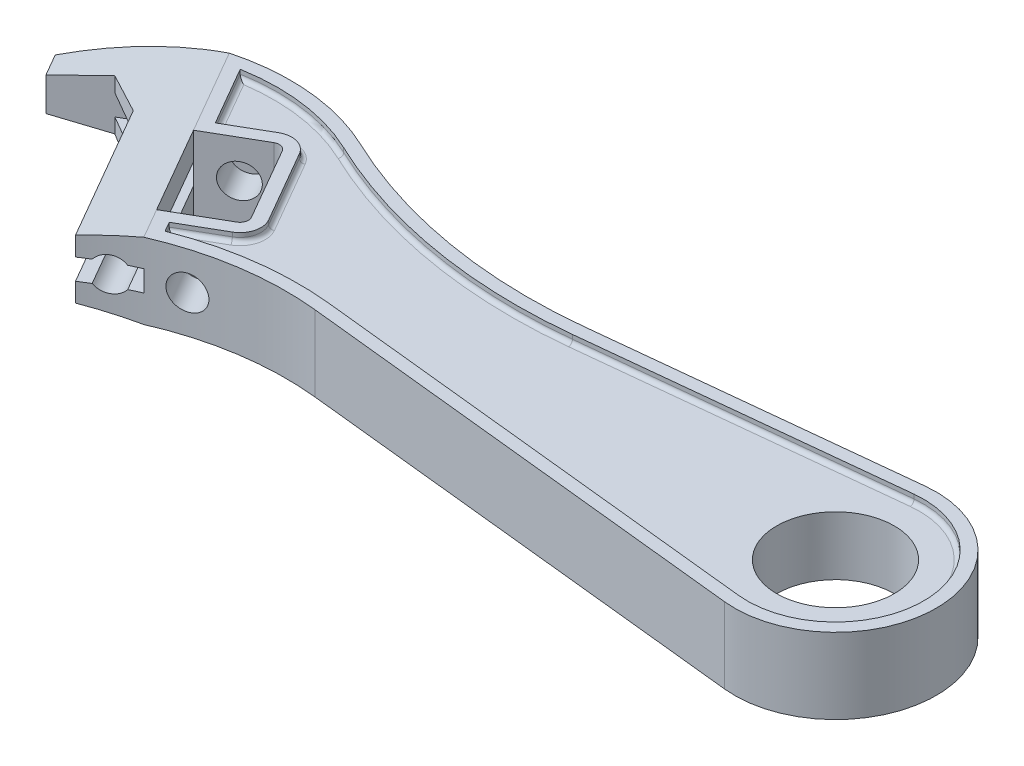
SolidWorks part; units mm, degrees
ref_plane "Front Plane" through (0, 0, 0) normal (0, 0, 1) x (1, 0, 0)
ref_plane "Top Plane" through (0, 0, 0) normal (0, 1, 0) x (1, 0, 0)
ref_plane "Right Plane" through (0, 0, 0) normal (1, 0, 0) x (0, 0, -1)
sketch "Sketch1" plane through (0, 0, 0) normal (0, 1, 0) x (1, 0, 0)
  line L0 (-38.0501, 8.0669) -> (-1.2543, 11.9343)
  line L1 (-55.796, -6.2017) -> (-1.2543, -11.9343)
  line L2 (25.0779, 0) -> (-99.2521, 0) construction
  line L3 (-74.5814, 9.0764) -> (-68.5814, -1.3159)
  line L4 (-68.5814, -1.3159) -> (-75.5096, -5.3159)
  line L5 (-75.5096, -5.3159) -> (-81.5096, 5.0764)
  line L6 (-81.5096, 5.0764) -> (-74.5814, 9.0764)
  line L7 (-87.3276, 15.1534) -> (-73.4285, -8.9206)
  line L8 (-78.7058, -11.78) -> (-88.1077, 4.5046)
  line L9 (-88.1077, 4.5046) -> (-93.3038, 7.5046)
  line L10 (-93.3038, 7.5046) -> (-98.5, 4.5046)
  line L11 (-98.5, 4.5046) -> (-100, 7.1027)
  line L12 (-93.3038, 7.5046) -> (-100.748, 20.3983) construction
  line L13 (-101.2059, 16) -> (-33.4804, 16) construction
  line L14 (-18.4207, -12) -> (11.6425, -12) construction
  line L15 (-90.2318, 14.1836) -> (-76.1316, -10.2386) construction
  line L16 (12, -12.8198) -> (12, 13.5746) construction
  line L17 (-100, 22.224) -> (-100, -5.3159) construction
  circle A0 centre (0, 0) radius 7
  arc A1 (-1.2543, -11.9343) -> (-1.2543, 11.9343) centre (0, 0) ccw
  arc A2 (-38.0501, 8.0669) -> (-70.1252, 13.5701) centre (-44.3218, 67.7382) cw
  arc A3 (-55.796, -6.2017) -> (-78.7058, -11.78) centre (-59.4545, -41.01) ccw
  arc A4 (-100, 7.1027) -> (-70.1252, 13.5701) centre (-80.8766, -9) cw
  point P31 (-72.0455, -3.3159)
  point P32 (-78.0455, 7.0764)
  dimension "D1" = 14
  dimension "D2" = 5
  dimension "D5" = 60
  dimension "D6" = 35
  dimension "D13" = 25
  dimension "D3" = 12
  dimension "D4" = 6
  dimension "D7" = 8
  dimension "D8" = 6
  dimension "D9" = 3
  dimension "D10" = 30
  dimension "D11" = 15
  dimension "D12" = 6
  dimension "D14" = 16
  dimension "D15" = 8
  dimension "D16" = 4
  dimension "D17" = 12
  dimension "D18" = 0.49
  dimension "D19" = 28
  dimension "D20" = 60
  dimension "D21" = 19
  dimension "D22" = 6
  dimension "D23" = 3
  dimension "D24" = 12
  dimension "D25" = 112
extrude "Boss-Extrude1" add sketch "Sketch1" along normal mid plane 9 contours A4 L7 L6 L3 L4 A3 L1 A1 L0 A2 A0 | A4 L11 L10 L9 L8 A3 L7 L5
sketch "Sketch2" plane through (-22.5755, 0, -39.102) normal (0.5, 0, 0.866) x (0.866, 0, -0.5)
  line L0 (0, 0) -> (-77.8625, 0) construction
  line L1 (-64.0512, 0) -> (-64.0512, 4.5) construction
  line L2 (-68.0512, 4.5) -> (-60.0512, 4.5) construction
  line L3 (-68.0512, 4.5) -> (-68.0512, -4.5) construction
  line L4 (-60.0512, 4.5) -> (-60.0512, -4.5) construction
  circle A0 centre (-64.0512, 0) radius 2
  dimension "D1" = 4
  dimension "D2" = 4
  dimension "D3" = 4
extrude "Cut-Extrude1" cut sketch "Sketch2" against normal blind 4 and the other way up to surface other way up to face at (-67.4929, 0, 7.9972)
sketch "Sketch3" plane through (-26.5755, 0, -46.0302) normal (0.5, 0, 0.866) x (0.866, 0, -0.5)
  line L0 (-83.0512, 0) -> (-56.4357, 0) construction
  line L1 (-83.0512, 4.5) -> (-83.0512, -4.5) construction
  line L2 (-77.0512, 1.25) -> (-72.6125, 1.25)
  line L4 (-77.0512, 4.5) -> (-77.0512, -4.5) construction
  line L5 (-77.0512, -1.25) -> (-72.6125, -1.25)
  line L6 (-69.49, 1.25) -> (-68.0512, 1.25)
  line L7 (-68.0512, 1.25) -> (-68.0512, -1.25)
  line L8 (-69.49, -1.25) -> (-68.0512, -1.25)
  circle A0 centre (-71.0512, 0) radius 2
  line M10 (-77.0512, -4.5) -> (-77.0512, 4.5)
  dimension "D1" = 4
  dimension "D2" = 2.5
  dimension "D3" = 2.5
  dimension "D4" = 15
  dimension "D5" = 12
extrude "Cut-Extrude2" cut sketch "Sketch3" along normal up to next contours A0 L0 | L0 A0 | L0 A0 L2 M10 | L0 L5 A0 M10 | A0 L0 L7 L6 | L0 A0 L8 L7
sketch "Sketch4" plane through (-26.5755, 0, -46.0302) normal (0.5, 0, 0.866) x (0.866, 0, -0.5)
  line L0 (-68.0512, 4.5) -> (-83.0512, 4.5)
  line L2 (-83.0512, 4.5) -> (-83.0512, -4.5) construction
  line L3 (-77.0512, 4.5) -> (-83.0512, 4.5) construction
  line L4 (-68.0512, 4.5) -> (-83.0512, 2)
  line L5 (-83.0512, 2) -> (-83.0512, 4.5)
  line L6 (0, 0) -> (-76.6034, 0) construction
  line L7 (-68.0512, -4.5) -> (-83.0512, -4.5)
  line L8 (-83.0512, -2) -> (-83.0512, -4.5)
  line L9 (-68.0512, -4.5) -> (-83.0512, -2)
  dimension "D1" = 15
  dimension "D2" = 2.5
extrude "Cut-Extrude3" cut sketch "Sketch4" against normal through all both and the other way through all
fillet "Fillet1" radius 1 2 edges at (-68.5814, 0, 1.3159) (-74.5814, 0, -9.0764)
sketch "Sketch5" plane through (0, 4.5, 0) normal (0, 1, 0) x (1, 0, 0)
  line L14 (-85.0071, 14.1342) -> (-80.9606, 7.1254)
  line L15 (-80.9606, 7.1254) -> (-76.1974, 9.8754)
  line L16 (-72.7824, 8.9604) -> (-67.7824, 0.3001)
  line L17 (-68.6974, -3.1149) -> (-73.4606, -5.8649)
  line L18 (-73.4606, -5.8649) -> (-72.7868, -7.032)
  line L19 (-55.6393, -4.7099) -> (-1.0975, -10.4425)
  line L20 (-1.0975, 10.4425) -> (-37.8933, 6.5751)
  line L21 (-85.0071, 14.1342) -> (-80.9606, 7.1254)
  line L22 (-80.9606, 7.1254) -> (-76.1974, 9.8754)
  line L23 (-72.7824, 8.9604) -> (-67.7824, 0.3001)
  line L24 (-68.6974, -3.1149) -> (-73.4606, -5.8649)
  line L25 (-73.4606, -5.8649) -> (-72.7868, -7.032)
  line L26 (-55.6393, -4.7099) -> (-1.0975, -10.4425)
  line L27 (-1.0975, 10.4425) -> (-37.8933, 6.5751)
  arc A12 (-70.7703, 12.2159) -> (-85.0071, 14.1342) centre (-80.8766, -9) ccw
  arc A13 (-72.7824, 8.9604) -> (-76.1974, 9.8754) centre (-74.9474, 7.7104) ccw
  arc A14 (-68.6974, -3.1149) -> (-67.7824, 0.3001) centre (-69.9474, -0.9499) ccw
  arc A15 (-55.6393, -4.7099) -> (-72.7868, -7.032) centre (-59.4545, -41.01) ccw
  arc A16 (-1.0975, -10.4425) -> (-1.0975, 10.4425) centre (0, 0) ccw
  arc A17 (-70.7703, 12.2159) -> (-37.8933, 6.5751) centre (-44.3218, 67.7382) ccw
  arc A18 (-70.7703, 12.2159) -> (-85.0071, 14.1342) centre (-80.8766, -9) ccw
  arc A19 (-72.7824, 8.9604) -> (-76.1974, 9.8754) centre (-74.9474, 7.7104) ccw
  arc A20 (-68.6974, -3.1149) -> (-67.7824, 0.3001) centre (-69.9474, -0.9499) ccw
  arc A21 (-55.6393, -4.7099) -> (-72.7868, -7.032) centre (-59.4545, -41.01) ccw
  arc A22 (-1.0975, -10.4425) -> (-1.0975, 10.4425) centre (0, 0) ccw
  arc A23 (-70.7703, 12.2159) -> (-37.8933, 6.5751) centre (-44.3218, 67.7382) ccw
  dimension "D1" = 1.5
extrude "Cut-Extrude4" cut sketch "Sketch5" against normal blind 1
fillet "Fillet2" radius 0.5 13 edges at (-64.3526, 3.5, 4.8401) (-28.3684, 3.5, 7.5762) (10.5, 3.5, 0) (-19.4954, 3.5, -8.5088) (-77.7385, 3.5, -14.2895) (-54.7216, 3.5, -7.1239) (-78.579, 3.5, -8.5004) (-74.3004, 3.5, -10.1252) (-71.079, 3.5, 4.4899) (-67.5326, 3.5, 1.5969) (-82.9838, 3.5, -10.6298) (-73.1237, 3.5, 6.4485) (-70.2824, 3.5, -4.6302)
mirror "Mirror1" about plane through (0, 0, 0) normal (0, 1, 0) of "Fillet2", "Cut-Extrude4"
